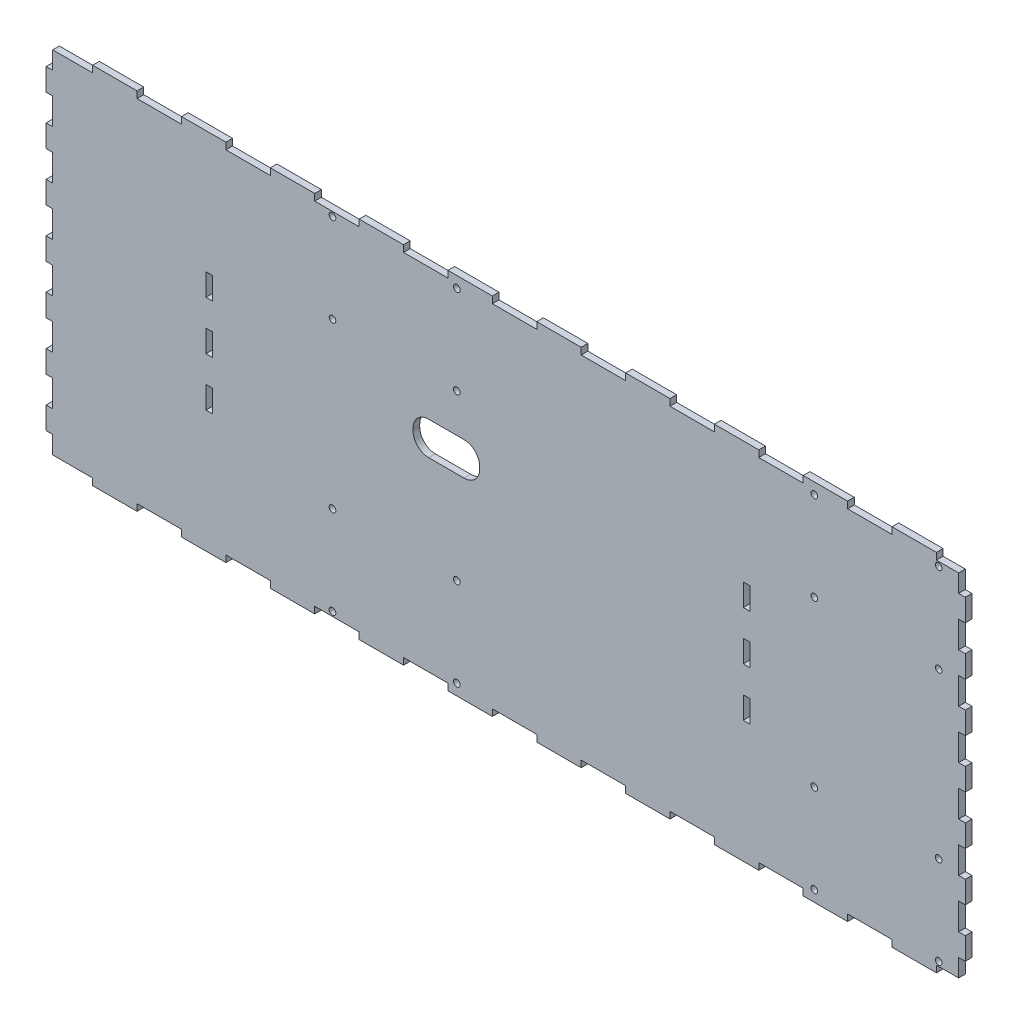
SolidWorks part; units mm, degrees
material "birch 3mm plywood"
ref_plane "Front Plane" through (0, 0, 0) normal (0, 0, 1) x (1, 0, 0)
ref_plane "Top Plane" through (0, 0, 0) normal (0, 1, 0) x (1, 0, 0)
ref_plane "Right Plane" through (0, 0, 0) normal (1, 0, 0) x (0, 0, -1)
sketch "Sketch1" plane through (0, 0, 152) normal (0, 0, 1) x (1, 0, 0)
  line L1 (-207, 82) -> (207, 82)
  line L2 (-207, 82) -> (-207, -82)
  line L3 (-207, -82) -> (207, -82)
  line L4 (207, 82) -> (207, -82)
  line L12 (200, -75) -> (-200, -75) construction
  line L13 (200, 75) -> (200, -75) construction
  line L14 (-200, -75) -> (-200, 75) construction
  line L15 (-200, 75) -> (200, 75) construction
  line L26 (-200, 0) -> (200, 0) construction
  line L31 (-200, 0) -> (200, 0) construction
  point P14 (0, 0)
  point P15 (0, 0)
  point P32 (-47.5, -25.9413)
  point P35 (256.981, -145.9413)
  point P38 (10.8894, 25.9413)
  point P51 (10.8894, -25.9413)
  point P54 (256.981, 145.9413)
  dimension "D1" = 7
  dimension "D2" = 7
  dimension "D3" = 7
  dimension "D4" = 7
  dimension "D5" = 150
  dimension "D6" = 400
extrude "Boss-Extrude1" add sketch "Sketch1" along normal blind 3
sketch "Sketch2" plane through (-207, 0, 0) normal (-1, 0, 0) x (0, 0, 1)
  line L7 (155, -82) -> (152, -82)
  line L8 (152, -82) -> (152, -71)
  line L9 (152, 82) -> (155, 82)
  line L10 (155, 82) -> (155, 71)
  line L11 (152, -61) -> (152, -49)
  line L12 (155, -71) -> (155, -82)
  line L13 (155, -49) -> (155, -61)
  line L14 (152, -39) -> (152, -27)
  line L15 (152, -17) -> (152, -5)
  line L16 (155, -27) -> (155, -39)
  line L17 (155, -5) -> (155, -17)
  line L18 (152, 5) -> (152, 17)
  line L19 (152, 27) -> (152, 39)
  line L20 (155, 17) -> (155, 5)
  line L21 (155, 39) -> (155, 27)
  line L22 (152, 49) -> (152, 61)
  line L23 (152, 71) -> (152, 82)
  line L24 (155, 61) -> (155, 49)
  line L76 (132.5, 88.6) -> (132.5, 93.6)
  line L77 (132.5, 88.6) -> (132.5, 93.6)
  line L78 (129.5, 98.6) -> (128.8771, 98.6)
  line L79 (129.5, 98.6) -> (128.8771, 98.6)
  line L80 (129.5, 82) -> (129.5, 88.6)
  line L81 (129.5, 82) -> (129.5, 88.6)
  line L82 (129.5, 88.6) -> (132.5, 88.6)
  line L83 (129.5, 88.6) -> (132.5, 88.6)
  line L85 (16, 82) -> (16, -82)
  line L102 (129.5, -82) -> (133, -82)
  line L103 (133, -82) -> (133, -79)
  line L104 (133, -79) -> (145, -79)
  line L105 (145, -79) -> (145, -82)
  line L106 (145, -82) -> (155, -82)
  line L107 (155, -82) -> (155, -71)
  line L108 (155, -71) -> (152, -71)
  line L109 (152, -71) -> (152, -61)
  line L110 (152, -61) -> (155, -61)
  line L111 (155, -61) -> (155, -49)
  line L112 (155, -49) -> (152, -49)
  line L113 (152, -49) -> (152, -39)
  line L114 (152, -39) -> (155, -39)
  line L115 (155, -39) -> (155, -27)
  line L116 (155, -27) -> (152, -27)
  line L117 (152, -27) -> (152, -17)
  line L118 (152, -17) -> (155, -17)
  line L119 (155, -17) -> (155, -5)
  line L120 (155, -5) -> (152, -5)
  line L121 (152, -5) -> (152, 5)
  line L122 (152, 5) -> (155, 5)
  line L123 (155, 5) -> (155, 17)
  line L124 (155, 17) -> (152, 17)
  line L125 (152, 17) -> (152, 27)
  line L126 (152, 27) -> (155, 27)
  line L127 (155, 27) -> (155, 39)
  line L128 (155, 39) -> (152, 39)
  line L129 (152, 39) -> (152, 49)
  line L130 (152, 49) -> (155, 49)
  line L131 (155, 49) -> (155, 61)
  line L132 (155, 61) -> (152, 61)
  line L133 (152, 61) -> (152, 71)
  line L134 (152, 71) -> (155, 71)
  line L135 (155, 71) -> (155, 82)
  line L136 (155, 82) -> (145, 82)
  line L137 (145, 82) -> (145, 79)
  line L138 (145, 79) -> (133, 79)
  line L139 (133, 79) -> (133, 82)
  line L140 (133, 82) -> (129.5, 82)
  line L184 (155, -71) -> (152, -71)
  line L186 (152, -61) -> (155, -61)
  line L188 (155, -49) -> (152, -49)
  line L190 (152, -39) -> (155, -39)
  line L192 (155, -27) -> (152, -27)
  line L194 (152, -17) -> (155, -17)
  line L196 (155, -5) -> (152, -5)
  line L198 (152, 5) -> (155, 5)
  line L200 (155, 17) -> (152, 17)
  line L202 (152, 27) -> (155, 27)
  line L204 (155, 39) -> (152, 39)
  line L206 (152, 49) -> (155, 49)
  line L208 (155, 61) -> (152, 61)
  line L210 (152, 71) -> (155, 71)
  line L297 (132.5, 93.6) -> (129.5, 93.6)
  line L298 (132.5, 93.6) -> (129.5, 93.6)
  line L299 (129.5, 93.6) -> (129.5, 98.6)
  line L300 (129.5, 93.6) -> (129.5, 98.6)
  line L301 (128.8771, -98.6) -> (129.5, -98.6)
  line L302 (128.8771, -98.6) -> (129.5, -98.6)
  line L303 (129.5, -98.6) -> (129.5, -93.6)
  line L304 (129.5, -98.6) -> (129.5, -93.6)
  line L305 (129.5, -93.6) -> (132.5, -93.6)
  line L306 (129.5, -93.6) -> (132.5, -93.6)
  line L307 (132.5, -93.6) -> (132.5, -88.6)
  line L308 (132.5, -93.6) -> (132.5, -88.6)
  line L309 (132.5, -88.6) -> (129.5, -88.6)
  line L310 (132.5, -88.6) -> (129.5, -88.6)
  line L311 (129.5, -88.6) -> (129.5, -82)
  line L312 (129.5, -88.6) -> (129.5, -82)
  arc A4 (128.8771, 98.6) -> (16, 82) centre (128.8771, -293.4723) ccw
  arc A5 (128.8771, 98.6) -> (16, 82) centre (128.8771, -293.4723) ccw
  arc A6 (16, -82) -> (128.8771, -98.6) centre (128.8771, 293.4723) ccw
  arc A7 (16, -82) -> (128.8771, -98.6) centre (128.8771, 293.4723) ccw
  line M77 (152, 82) -> (152, -82)
  line M78 (152, -82) -> (155, -82)
  line M79 (155, -82) -> (155, 82)
  line M80 (155, 82) -> (152, 82)
  dimension "D1" = 0
extrude "Cut-Extrude1" cut sketch "Sketch2" against normal blind 3 contours L184 M79 M77 M78 | L188 L186 M79 M77 | L192 L190 M79 M77 | L196 L194 M79 M77 | L200 L198 M79 M77 | L204 L202 M79 M77 | L208 L206 M79 M77 | L210 M77 M79 M80
mirror "Mirror1" about plane through (0, 0, 0) normal (1, 0, 0) of "Cut-Extrude1"
sketch "Sketch3" plane through (0, 82, 0) normal (0, 1, 0) x (1, 0, 0)
  line L92 (174, -152) -> (194, -152)
  line L93 (194, -152) -> (194, -155)
  line L94 (194, -155) -> (204, -155)
  line L97 (207, -45) -> (204, -45)
  line L120 (204, -16) -> (-204, -16)
  line L123 (-204, -45) -> (-207, -45)
  line L146 (-204, -155) -> (-186, -155)
  line L147 (-186, -155) -> (-186, -152)
  line L148 (-186, -152) -> (-166, -152)
  line L149 (-166, -152) -> (-166, -155)
  line L150 (-166, -155) -> (-146, -155)
  line L151 (-146, -155) -> (-146, -152)
  line L152 (-146, -152) -> (-126, -152)
  line L153 (-126, -152) -> (-126, -155)
  line L154 (-126, -155) -> (-106, -155)
  line L155 (-106, -155) -> (-106, -152)
  line L156 (-106, -152) -> (-86, -152)
  line L157 (-86, -152) -> (-86, -155)
  line L158 (-86, -155) -> (-66, -155)
  line L159 (-66, -155) -> (-66, -152)
  line L160 (-66, -152) -> (-46, -152)
  line L161 (-46, -152) -> (-46, -155)
  line L162 (-46, -155) -> (-26, -155)
  line L163 (-26, -155) -> (-26, -152)
  line L164 (-26, -152) -> (-6, -152)
  line L165 (-6, -152) -> (-6, -155)
  line L166 (-6, -155) -> (14, -155)
  line L167 (14, -155) -> (14, -152)
  line L168 (14, -152) -> (34, -152)
  line L169 (34, -152) -> (34, -155)
  line L170 (34, -155) -> (54, -155)
  line L171 (54, -155) -> (54, -152)
  line L172 (54, -152) -> (74, -152)
  line L173 (74, -152) -> (74, -155)
  line L174 (74, -155) -> (94, -155)
  line L175 (94, -155) -> (94, -152)
  line L176 (94, -152) -> (114, -152)
  line L177 (114, -152) -> (114, -155)
  line L178 (114, -155) -> (134, -155)
  line L179 (134, -155) -> (134, -152)
  line L180 (134, -152) -> (154, -152)
  line L181 (154, -152) -> (154, -155)
  line L182 (154, -155) -> (174, -155)
  line L183 (174, -155) -> (174, -152)
  line L184 (174, -152) -> (194, -152)
  line L185 (194, -152) -> (194, -155)
  line L186 (194, -155) -> (204, -155)
  line L212 (204, -16) -> (-204, -16)
  line L238 (-204, -155) -> (-186, -155)
  line L239 (-186, -155) -> (-186, -152)
  line L240 (-186, -152) -> (-166, -152)
  line L241 (-166, -152) -> (-166, -155)
  line L242 (-166, -155) -> (-146, -155)
  line L243 (-146, -155) -> (-146, -152)
  line L244 (-146, -152) -> (-126, -152)
  line L245 (-126, -152) -> (-126, -155)
  line L246 (-126, -155) -> (-106, -155)
  line L247 (-106, -155) -> (-106, -152)
  line L248 (-106, -152) -> (-86, -152)
  line L249 (-86, -152) -> (-86, -155)
  line L250 (-86, -155) -> (-66, -155)
  line L251 (-66, -155) -> (-66, -152)
  line L252 (-66, -152) -> (-46, -152)
  line L253 (-46, -152) -> (-46, -155)
  line L254 (-46, -155) -> (-26, -155)
  line L255 (-26, -155) -> (-26, -152)
  line L256 (-26, -152) -> (-6, -152)
  line L257 (-6, -152) -> (-6, -155)
  line L258 (-6, -155) -> (14, -155)
  line L259 (14, -155) -> (14, -152)
  line L260 (14, -152) -> (34, -152)
  line L261 (34, -152) -> (34, -155)
  line L262 (34, -155) -> (54, -155)
  line L263 (54, -155) -> (54, -152)
  line L264 (54, -152) -> (74, -152)
  line L265 (74, -152) -> (74, -155)
  line L266 (74, -155) -> (94, -155)
  line L267 (94, -155) -> (94, -152)
  line L268 (94, -152) -> (114, -152)
  line L269 (114, -152) -> (114, -155)
  line L270 (114, -155) -> (134, -155)
  line L271 (134, -155) -> (134, -152)
  line L272 (134, -152) -> (154, -152)
  line L273 (154, -152) -> (154, -155)
  line L274 (154, -155) -> (174, -155)
  line L275 (174, -155) -> (174, -152)
  line L576 (-204, -45) -> (-207, -45)
  line L577 (-207, -45) -> (-207, -57)
  line L578 (-207, -45) -> (-207, -57)
  line L579 (-207, -57) -> (-204, -57)
  line L580 (-207, -57) -> (-204, -57)
  line L581 (-204, -57) -> (-204, -67)
  line L582 (-204, -57) -> (-204, -67)
  line L583 (-204, -67) -> (-207, -67)
  line L584 (-204, -67) -> (-207, -67)
  line L585 (-207, -67) -> (-207, -79)
  line L586 (-207, -67) -> (-207, -79)
  line L587 (-207, -79) -> (-204, -79)
  line L588 (-207, -79) -> (-204, -79)
  line L589 (-204, -79) -> (-204, -89)
  line L590 (-204, -79) -> (-204, -89)
  line L591 (-204, -89) -> (-207, -89)
  line L592 (-204, -89) -> (-207, -89)
  line L593 (-207, -89) -> (-207, -101)
  line L594 (-207, -89) -> (-207, -101)
  line L595 (-207, -101) -> (-204, -101)
  line L596 (-207, -101) -> (-204, -101)
  line L597 (-204, -101) -> (-204, -111)
  line L598 (-204, -101) -> (-204, -111)
  line L599 (-204, -111) -> (-207, -111)
  line L600 (-204, -111) -> (-207, -111)
  line L601 (-207, -111) -> (-207, -123)
  line L602 (-207, -111) -> (-207, -123)
  line L603 (-207, -123) -> (-204, -123)
  line L604 (-207, -123) -> (-204, -123)
  line L605 (-204, -123) -> (-204, -133)
  line L606 (-204, -123) -> (-204, -133)
  line L607 (-204, -133) -> (-207, -133)
  line L608 (-204, -133) -> (-207, -133)
  line L609 (-207, -133) -> (-207, -145)
  line L610 (-207, -133) -> (-207, -145)
  line L611 (-207, -145) -> (-204, -145)
  line L612 (-207, -145) -> (-204, -145)
  line L613 (-204, -145) -> (-204, -155)
  line L614 (-204, -145) -> (-204, -155)
  line L615 (-204, -16) -> (-204, -23)
  line L616 (-204, -16) -> (-204, -23)
  line L617 (-204, -23) -> (-207, -23)
  line L618 (-204, -23) -> (-207, -23)
  line L619 (-207, -23) -> (-207, -35)
  line L620 (-207, -23) -> (-207, -35)
  line L621 (-207, -35) -> (-204, -35)
  line L622 (-207, -35) -> (-204, -35)
  line L623 (-204, -35) -> (-204, -45)
  line L624 (-204, -35) -> (-204, -45)
  line L741 (207, -45) -> (204, -45)
  line L742 (204, -45) -> (204, -35)
  line L743 (204, -45) -> (204, -35)
  line L744 (204, -35) -> (207, -35)
  line L745 (204, -35) -> (207, -35)
  line L746 (207, -35) -> (207, -23)
  line L747 (207, -35) -> (207, -23)
  line L748 (207, -23) -> (204, -23)
  line L749 (207, -23) -> (204, -23)
  line L750 (204, -23) -> (204, -16)
  line L751 (204, -23) -> (204, -16)
  line L752 (204, -155) -> (204, -145)
  line L753 (204, -155) -> (204, -145)
  line L754 (204, -145) -> (207, -145)
  line L755 (204, -145) -> (207, -145)
  line L756 (207, -145) -> (207, -133)
  line L757 (207, -145) -> (207, -133)
  line L758 (207, -133) -> (204, -133)
  line L759 (207, -133) -> (204, -133)
  line L760 (204, -133) -> (204, -123)
  line L761 (204, -133) -> (204, -123)
  line L762 (204, -123) -> (207, -123)
  line L763 (204, -123) -> (207, -123)
  line L764 (207, -123) -> (207, -111)
  line L765 (207, -123) -> (207, -111)
  line L766 (207, -111) -> (204, -111)
  line L767 (207, -111) -> (204, -111)
  line L768 (204, -111) -> (204, -101)
  line L769 (204, -111) -> (204, -101)
  line L770 (204, -101) -> (207, -101)
  line L771 (204, -101) -> (207, -101)
  line L772 (207, -101) -> (207, -89)
  line L773 (207, -101) -> (207, -89)
  line L774 (207, -89) -> (204, -89)
  line L775 (207, -89) -> (204, -89)
  line L776 (204, -89) -> (204, -79)
  line L777 (204, -89) -> (204, -79)
  line L778 (204, -79) -> (207, -79)
  line L779 (204, -79) -> (207, -79)
  line L780 (207, -79) -> (207, -67)
  line L781 (207, -79) -> (207, -67)
  line L782 (207, -67) -> (204, -67)
  line L783 (207, -67) -> (204, -67)
  line L784 (204, -67) -> (204, -57)
  line L785 (204, -67) -> (204, -57)
  line L786 (204, -57) -> (207, -57)
  line L787 (204, -57) -> (207, -57)
  line L788 (207, -57) -> (207, -45)
  line L789 (207, -57) -> (207, -45)
  dimension "D1" = 0
extrude "Cut-Extrude2" cut sketch "Sketch3" against normal blind 3
mirror "Mirror2" about plane through (0, 0, 0) normal (0, 1, 0) of "Cut-Extrude2"
sketch "Sketch4" plane through (0, 0, 155) normal (0, 0, 1) x (1, 0, 0)
  line L0 (-132, 27) -> (-132, 17) construction
  line L1 (-132, 17) -> (-135, 17) construction
  line L2 (-135, 17) -> (-135, 27) construction
  line L3 (-135, 27) -> (-132, 27) construction
  line L4 (-132, 5) -> (-132, -5) construction
  line L5 (-132, -5) -> (-135, -5) construction
  line L6 (-135, -5) -> (-135, 5) construction
  line L7 (-135, 5) -> (-132, 5) construction
  line L8 (-132, -17) -> (-132, -27) construction
  line L9 (-132, -27) -> (-135, -27) construction
  line L10 (-135, -27) -> (-135, -17) construction
  line L11 (-135, -17) -> (-132, -17) construction
  line L12 (-132, 27) -> (-132, 17)
  line L13 (-132, 17) -> (-135, 17)
  line L14 (-135, 17) -> (-135, 27)
  line L15 (-135, 27) -> (-132, 27)
  line L16 (-132, 5) -> (-132, -5)
  line L17 (-132, -5) -> (-135, -5)
  line L18 (-135, -5) -> (-135, 5)
  line L19 (-135, 5) -> (-132, 5)
  line L20 (-132, -17) -> (-132, -27)
  line L21 (-132, -27) -> (-135, -27)
  line L22 (-135, -27) -> (-135, -17)
  line L23 (-135, -17) -> (-132, -17)
  line L24 (110, 27) -> (110, 17) construction
  line L25 (110, 17) -> (107, 17) construction
  line L26 (107, 17) -> (107, 27) construction
  line L27 (107, 27) -> (110, 27) construction
  line L28 (110, 5) -> (110, -5) construction
  line L29 (110, -5) -> (107, -5) construction
  line L30 (107, -5) -> (107, 5) construction
  line L31 (107, 5) -> (110, 5) construction
  line L32 (110, -17) -> (110, -27) construction
  line L33 (110, -27) -> (107, -27) construction
  line L34 (107, -27) -> (107, -17) construction
  line L35 (107, -17) -> (110, -17) construction
  line L36 (110, 27) -> (110, 17)
  line L37 (110, 17) -> (107, 17)
  line L38 (107, 17) -> (107, 27)
  line L39 (107, 27) -> (110, 27)
  line L40 (110, 5) -> (110, -5)
  line L41 (110, -5) -> (107, -5)
  line L42 (107, -5) -> (107, 5)
  line L43 (107, 5) -> (110, 5)
  line L44 (110, -17) -> (110, -27)
  line L45 (110, -27) -> (107, -27)
  line L46 (107, -27) -> (107, -17)
  line L47 (107, -17) -> (110, -17)
  line L80 (207, 0) -> (-207, 0) construction
  line L81 (207, -5) -> (207, 5) construction
  line L82 (-207, 5) -> (-207, -5) construction
  circle A0 centre (139, 37) radius 1.5 construction
  circle A1 centre (195, 37) radius 1.5 construction
  circle A2 centre (195, 77) radius 1.5 construction
  circle A3 centre (139, 77) radius 1.5 construction
  circle A4 centre (-78, 77) radius 1.5 construction
  circle A5 centre (-22, 77) radius 1.5 construction
  circle A6 centre (-78, 37) radius 1.5 construction
  circle A7 centre (-22, 37) radius 1.5 construction
  circle A8 centre (139, 37) radius 1.5
  circle A9 centre (195, 37) radius 1.5
  circle A10 centre (195, 77) radius 1.5
  circle A11 centre (139, 77) radius 1.5
  circle A12 centre (-78, 77) radius 1.5
  circle A13 centre (-22, 77) radius 1.5
  circle A14 centre (-78, 37) radius 1.5
  circle A15 centre (-22, 37) radius 1.5
  circle A16 centre (139, -77) radius 1.5
  circle A17 centre (195, -77) radius 1.5
  circle A18 centre (195, -37) radius 1.5
  circle A19 centre (139, -37) radius 1.5
  circle A20 centre (-22, -37) radius 1.5
  circle A21 centre (-78, -37) radius 1.5
  circle A22 centre (-22, -77) radius 1.5
  circle A23 centre (-78, -77) radius 1.5
extrude "Cut-Extrude3" cut sketch "Sketch4" against normal blind 10
sketch "Sketch5" plane through (0, 0, 155) normal (0, 0, 1) x (1, 0, 0)
  line L1 (-34.7, 4.6) -> (-18.7, 4.6)
  line L2 (-41.7, 11.6) -> (-41.7, 12.6)
  line L3 (-34.7, 19.6) -> (-18.7, 19.6)
  line L4 (-11.7, 12.6) -> (-11.7, 11.6)
  line L5 (-27.7, 4.6) -> (0, 4.6) construction
  line L7 (-27.7, 4.6) -> (-27.7, -7.8) construction
  arc A0 (-34.7, 19.6) -> (-41.7, 12.6) centre (-34.7, 12.6) ccw
  arc A1 (-11.7, 12.6) -> (-18.7, 19.6) centre (-18.7, 12.6) ccw
  arc A2 (-18.7, 4.6) -> (-11.7, 11.6) centre (-18.7, 11.6) ccw
  arc A3 (-34.7, 4.6) -> (-41.7, 11.6) centre (-34.7, 11.6) cw
  point P16 (-11.7, 4.6)
  point P19 (-41.7, 4.6)
  dimension "D4" = 7
  dimension "D1" = 30
  dimension "D2" = 15
  dimension "D3" = 16
extrude "Cut-Extrude4" cut sketch "Sketch5" against normal blind 10
